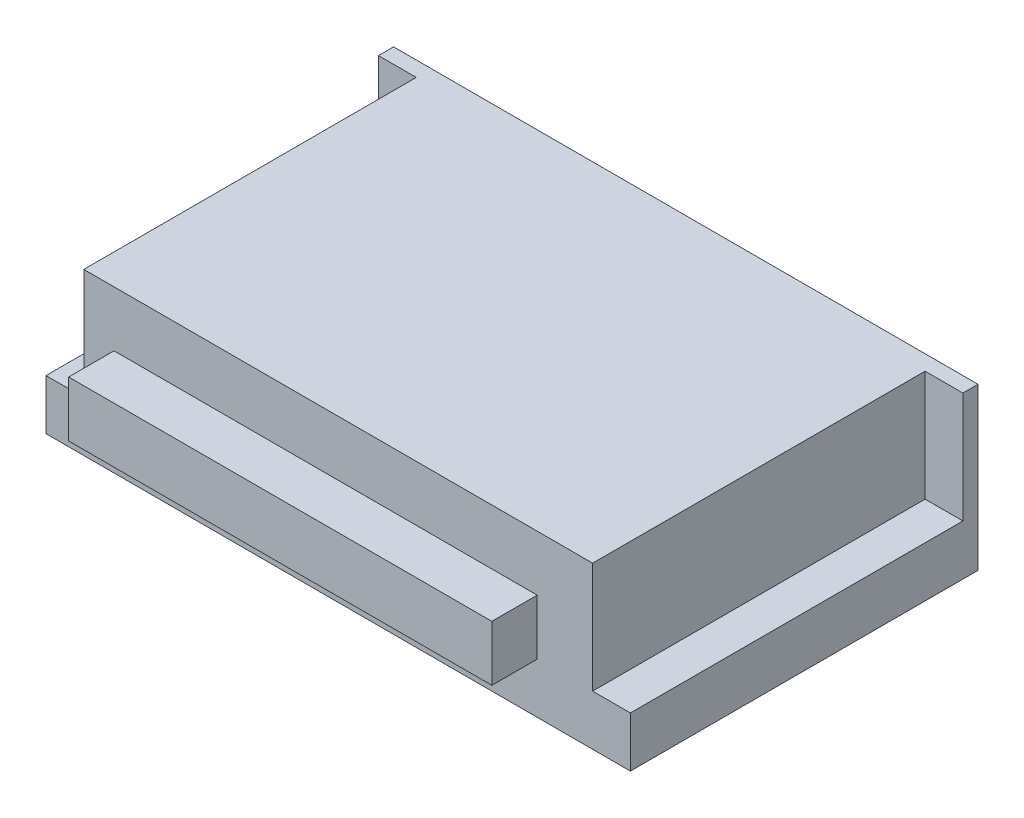
SolidWorks part; units mm, degrees
ref_plane "前视基准面" through (0, 0, 0) normal (0, 0, 1) x (1, 0, 0)
ref_plane "上视基准面" through (0, 0, 0) normal (0, 1, 0) x (1, 0, 0)
ref_plane "右视基准面" through (0, 0, 0) normal (1, 0, 0) x (0, 0, -1)
sketch "草图1" plane through (0, 0, 0) normal (0, 1, 0) x (1, 0, 0)
  line L1 (0, 0) -> (116, 0)
  line L2 (0, 0) -> (0, 69)
  line L3 (0, 69) -> (116, 69)
  line L4 (116, 0) -> (116, 69)
  dimension "D1" = 116
  dimension "D2" = 69
extrude "凸台-拉伸1" add sketch "草图1" along normal blind 32
sketch "草图2" plane through (0, 32, 0) normal (0, 1, 0) x (1, 0, 0)
  line L0 (116, 69) -> (0, 69) construction
  line L1 (116, 0) -> (108.5, 0)
  line L2 (116, 0) -> (116, 66)
  line L3 (116, 66) -> (108.5, 66)
  line L4 (108.5, 0) -> (108.5, 66)
  line L5 (0, 0) -> (7.5, 0)
  line L6 (0, 0) -> (0, 66)
  line L7 (0, 66) -> (7.5, 66)
  line L8 (7.5, 0) -> (7.5, 66)
  dimension "D1" = 7.5
  dimension "D2" = 7.5
  dimension "D3" = 3
extrude "切除-拉伸1" cut sketch "草图2" against normal blind 22
sketch "草图3" plane through (0, 0, 0) normal (0, 0, 1) x (1, 0, 0)
  line L0 (108.5, 10) -> (108.5, 32) construction
  line L1 (13.5, 10) -> (97.5, 10)
  line L2 (13.5, 10) -> (13.5, 21)
  line L3 (13.5, 21) -> (97.5, 21)
  line L4 (97.5, 10) -> (97.5, 21)
  line L5 (116, 10) -> (108.5, 10) construction
  dimension "D1" = 84
  dimension "D2" = 11
  dimension "D3" = 11
extrude "凸台-拉伸2" add sketch "草图3" along normal blind 9
